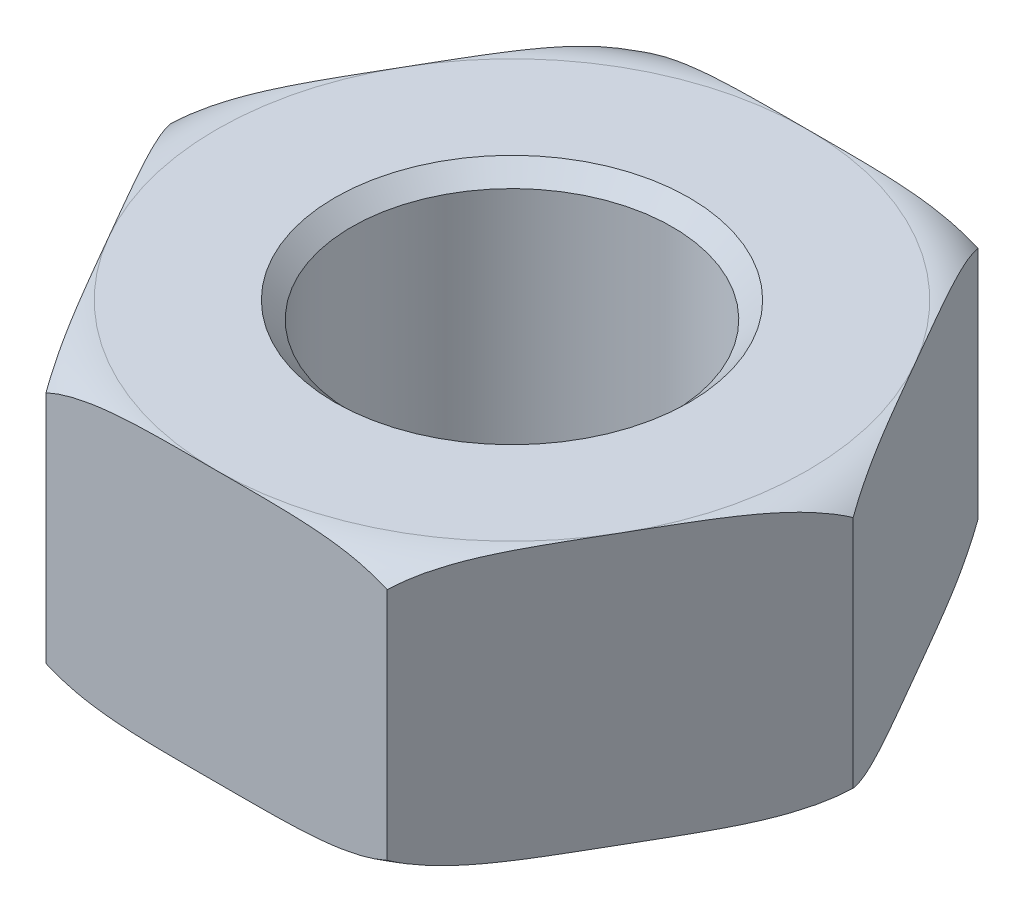
SolidWorks part; units mm, degrees
ref_plane "Front Plane" through (0, 0, 0) normal (0, 0, 1) x (1, 0, 0)
ref_plane "Top Plane" through (0, 0, 0) normal (0, 1, 0) x (1, 0, 0)
ref_plane "Right Plane" through (0, 0, 0) normal (1, 0, 0) x (0, 0, -1)
sketch "Sketch1" plane through (0, 0, 0) normal (0, 1, 0) x (1, 0, 0)
  line L1 (4.0415, 0) -> (2.0207, 3.5)
  line L2 (2.0207, 3.5) -> (-2.0207, 3.5)
  line L3 (-2.0207, 3.5) -> (-4.0415, 0)
  line L4 (-4.0415, 0) -> (-2.0207, -3.5)
  line L5 (-2.0207, -3.5) -> (2.0207, -3.5)
  line L6 (2.0207, -3.5) -> (4.0415, 0)
  circle A0 centre (0, 0) radius 3.5 construction
  circle A1 centre (0, 0) radius 1.9
  dimension "D1" = 3.8
  dimension "D2" = 7
extrude "Boss-Extrude1" add sketch "Sketch1" along normal mid plane 3.2
sketch "Sketch2" plane through (0, 0, 0) normal (0, 0, 1) x (1, 0, 0)
  line L1 (0, -1.6) -> (-4.0415, -1.6) construction
  line L2 (-2.0207, -1.6) -> (2.0207, -1.6) construction
  line L3 (-3.5, -1.6) -> (-3.5, 0) construction
  line L4 (-4.3, -0.8) -> (-4.3, -1.6)
  line L5 (-4.3, -1.6) -> (-3.5, -1.6)
  line L6 (0, 0) -> (0, 4.8499) construction
  arc A0 (-3.5, -1.6) -> (-4.3, -0.8) centre (-3.5, -0.8) cw
  dimension "D1" = 0.8
  dimension "D2" = 0.8
revolve "Cut-Revolve1" cut sketch "Sketch2" angle 360 about L6
mirror "Mirror2" about plane through (0, 0, 0) normal (0, 1, 0) of "Cut-Revolve1"
chamfer "Chamfer1" distance 0.2 angle 45 2 edges at (0, -1.6, 1.9) (0, 1.6, 1.9)
equation "\"D2@Sketch2\"=\"D1@Sketch2\""
